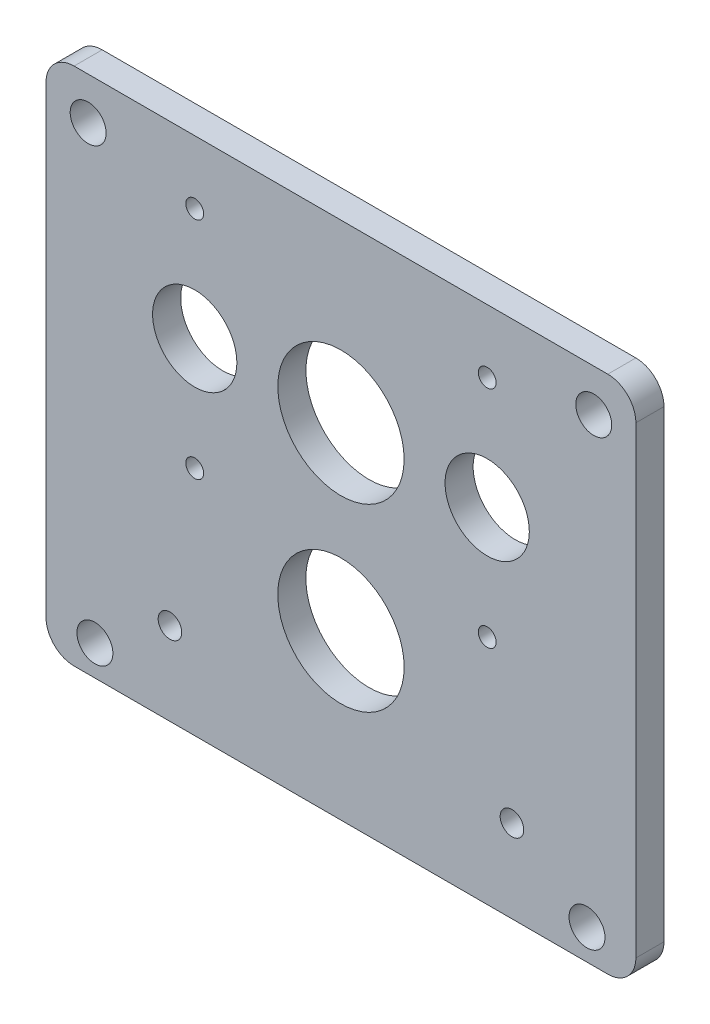
SolidWorks part; units mm, degrees
material "6061 Alloy"
ref_plane "Front Plane" through (0, 0, 0) normal (0, 0, 1) x (1, 0, 0)
ref_plane "Top Plane" through (0, 0, 0) normal (0, 1, 0) x (1, 0, 0)
ref_plane "Right Plane" through (0, 0, 0) normal (1, 0, 0) x (0, 0, -1)
sketch "Sketch1" plane through (0, 0, 0) normal (0, 0, 1) x (1, 0, 0)
  line L0 (-33.0581, 40.7162) -> (33.0581, 40.7162) construction
  line L1 (0, 40.7162) -> (0, 0) construction
  line L3 (-66.675, 80.4164) -> (66.675, 80.4164)
  line L4 (-66.675, 80.4164) -> (-66.675, -37.0586)
  line L5 (-66.675, -37.0586) -> (66.675, -37.0586)
  line L6 (66.675, 80.4164) -> (66.675, -37.0586)
  line L7 (-66.675, 80.4164) -> (66.675, -37.0586) construction
  line L8 (-66.675, -37.0586) -> (66.675, 80.4164) construction
  line L9 (-38.6588, -18.3134) -> (38.6588, -18.3134) construction
  line L10 (0, 70.5866) -> (0, -18.3134) construction
  circle A0 centre (0, 40.7162) radius 26.67 construction
  circle A1 centre (0, 40.7162) radius 25.4 construction
  circle A2 centre (-33.0581, 40.7162) radius 8.89 construction
  circle A3 centre (33.0581, 40.7162) radius 7.62 construction
  circle A4 centre (33.0581, 40.7162) radius 8.89 construction
  circle A5 centre (-33.0581, 40.7162) radius 7.62 construction
  circle A6 centre (0, 40.7162) radius 16.51 construction
  circle A7 centre (0, 40.7162) radius 15.24 construction
  circle A8 centre (0, 0) radius 26.67 construction
  circle A9 centre (0, 0) radius 25.4 construction
  circle A10 centre (0, 40.7162) radius 14.2748
  circle A11 centre (33.0581, 40.7162) radius 9.525
  circle A12 centre (-33.0581, 40.7162) radius 9.525
  circle A13 centre (-33.0581, 40.7162) radius 32.004 construction
  circle A14 centre (33.0581, 40.7162) radius 32.004 construction
  circle A15 centre (-33.0581, 40.7162) radius 25.4 construction
  circle A16 centre (33.0581, 40.7162) radius 25.4 construction
  circle A17 centre (-57.15, 70.8914) radius 9.525 construction
  circle A18 centre (57.15, 70.8914) radius 9.525 construction
  circle A19 centre (-33.0581, 66.1162) radius 2.0193
  circle A20 centre (-33.0581, 15.3162) radius 2.0193
  circle A21 centre (0, 0) radius 14.2875
  circle A22 centre (-57.15, 70.8914) radius 4.064
  circle A23 centre (-55.626, -30.2006) radius 4.064
  circle A24 centre (57.15, 70.8914) radius 4.064
  circle A25 centre (55.626, -30.2006) radius 4.064
  circle A26 centre (38.6588, -18.3134) radius 2.667
  circle A27 centre (-38.6588, -18.3134) radius 2.667
  circle A28 centre (33.0581, 66.1162) radius 2.0193
  circle A29 centre (33.0581, 15.3162) radius 2.0193
  point P31 (0, 21.6789)
  dimension "D1" = 53.34
  dimension "D2" = 50.8
  dimension "D3" = 15.24
  dimension "D4" = 17.78
  dimension "D6" = 30.48
  dimension "D7" = 33.02
  dimension "D9" = 28.5496
  dimension "D10" = 19.05
  dimension "D11" = 64.008
  dimension "D12" = 50.8
  dimension "D13" = 19.05
  dimension "D15" = 4.0386
  dimension "D16" = 5.334
  dimension "D17" = 28.575
  dimension "D21" = 8.128
  dimension "D22" = 55.626
  dimension "D5" = 66.1162
  dimension "D8" = 40.7162
  dimension "D14" = 133.35
  dimension "4" = 117.475
  dimension "D18" = 88.9
  dimension "D19" = 77.3176
  dimension "D20" = 18.3134
  dimension "D23" = 55.626
  dimension "D24" = 30.2006
  dimension "D25" = 30.2006
  dimension "D26" = 80.4164
extrude "Boss-Extrude1" add sketch "Sketch1" along normal mid plane 6.35
fillet "Fillet1" radius 6.35 4 edges at (66.675, 80.4164, 0) (66.675, -37.0586, 0) (-66.675, -37.0586, 0) (-66.675, 80.4164, 0)
